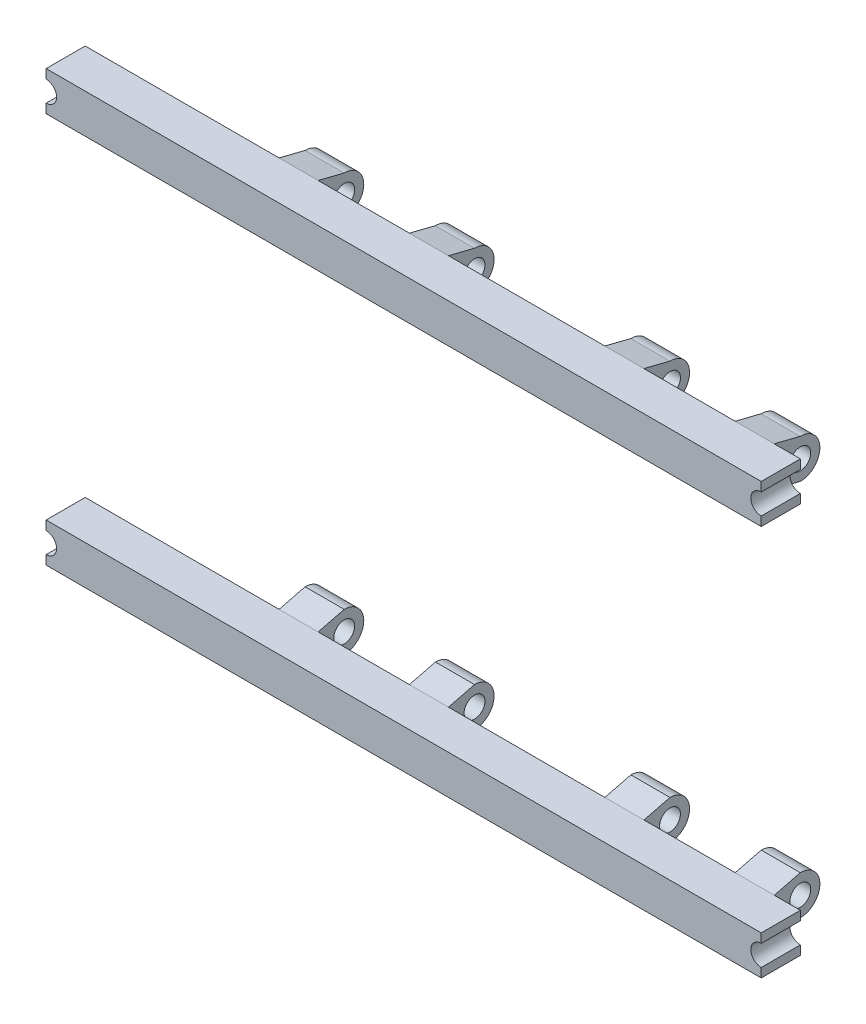
SolidWorks part; units mm, degrees
ref_plane "Front Plane" through (0, 0, 0) normal (0, 0, 1) x (1, 0, 0)
ref_plane "Top Plane" through (0, 0, 0) normal (0, 1, 0) x (1, 0, 0)
ref_plane "Right Plane" through (0, 0, 0) normal (1, 0, 0) x (0, 0, -1)
sketch "Sketch1" plane through (0, 0, 0) normal (0, 0, 1) x (1, 0, 0)
  line L1 (3, -220) -> (112.75, -220)
  line L2 (3, -220) -> (3, -214)
  line L3 (3, -214) -> (112.75, -214)
  line L4 (112.75, -220) -> (112.75, -214)
  line L6 (3, -214) -> (112.75, -220) construction
  line L7 (57.875, -217) -> (57.875, -159) construction
  line L8 (3, -159) -> (112.75, -159) construction
  line L10 (3, -154) -> (112.75, -154)
  line L11 (3, -154) -> (3, -160)
  line L12 (3, -160) -> (112.75, -160)
  line L13 (112.75, -154) -> (112.75, -160)
  point P12 (57.875, -159)
  dimension "D1" = 58
extrude "Boss-Extrude1" add sketch "Sketch1" against normal blind 6 contours L12 L13 L10 L11 | L1 L4 L3 L2
sketch "Sketch2" plane through (112.75, 0, 0) normal (1, 0, 0) x (0, 0, -1)
  line L0 (6, -214) -> (10, -213)
  line L1 (6, -220) -> (10, -219)
  line L2 (6, -220) -> (6, -214)
  line L3 (6, -214) -> (6, -160) construction
  line L4 (6, -187) -> (28.8077, -187) construction
  line L5 (6, -154) -> (6, -160)
  line L6 (6, -154) -> (10, -155)
  line L7 (6, -160) -> (10, -161)
  circle A0 centre (10, -216) radius 1.6
  arc A1 (8.5882, -160.6471) -> (10, -161) centre (10, -158) cw
  arc A2 (8.5882, -213.3529) -> (10, -213) centre (10, -216) ccw
  circle A3 centre (10, -158) radius 1.6
  line M9 (6, -160) -> (6, -154)
  dimension "D1" = 3.2
  dimension "D2" = 6
  dimension "D3" = 58
  dimension "D4" = 4
extrude "Boss-Extrude2" add sketch "Sketch2" against normal blind 6 from offset 4 contours L0 A2 A0 | A2 L0 L2 L1 | A1 L7 A3 | L7 A1 L6 M9 offset against normal yes
pattern_linear "LPattern1" count 8 spacing 10 along (-1, 0, 0) skipping (1, 0), (3, 0), (4, 0), (6, 0) of "Boss-Extrude2"
sketch "Sketch3" plane through (0, 0, 0) normal (0, 0, 1) x (1, 0, 0)
  line L0 (3, -220) -> (3, -214) construction
  line L1 (3, -154) -> (3, -160) construction
  line L2 (112.75, -154) -> (112.75, -160) construction
  line L4 (112.75, -220) -> (112.75, -214) construction
  circle A0 centre (3, -217) radius 1.6
  circle A1 centre (3, -157) radius 1.6
  circle A2 centre (112.75, -157) radius 1.6
  circle A3 centre (112.75, -217) radius 1.6
  dimension "D1" = 3.2
extrude "Cut-Extrude1" cut sketch "Sketch3" against normal up to next
